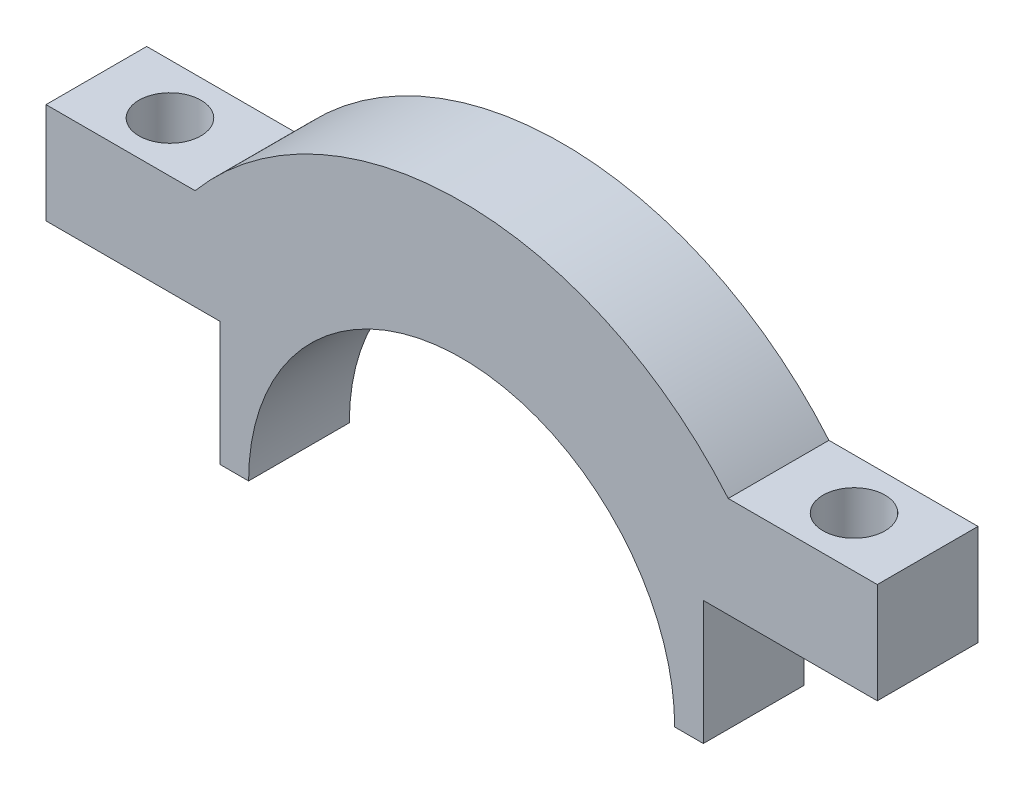
SolidWorks part; units mm, degrees
ref_plane "Front Plane" through (0, 0, 0) normal (0, 0, 1) x (1, 0, 0)
ref_plane "Top Plane" through (0, 0, 0) normal (0, 1, 0) x (1, 0, 0)
ref_plane "Right Plane" through (0, 0, 0) normal (1, 0, 0) x (0, 0, -1)
sketch "Sketch1" plane through (0, 0, 0) normal (0, 0, 1) x (1, 0, 0)
  line L0 (-27.5, 0) -> (-31.2, 0)
  line L1 (-31.2, 0) -> (-31.2, 16)
  line L2 (-31.2, 16) -> (-53.65, 16)
  line L3 (-53.65, 16) -> (-53.65, 29)
  line L4 (-53.65, 29) -> (-34.4093, 29)
  line L6 (27.5, 0) -> (31.2, 0)
  line L7 (31.2, 0) -> (31.2, 16)
  line L8 (31.2, 16) -> (53.65, 16)
  line L9 (53.65, 16) -> (53.65, 29)
  line L10 (53.65, 29) -> (34.4093, 29)
  arc A0 (27.5, 0) -> (-27.5, 0) centre (0, 0) ccw
  arc A1 (34.4093, 29) -> (-34.4093, 29) centre (0, 0) ccw
  dimension "D1" = 3.7
  dimension "D3" = 22.45
  dimension "D2" = 16
  dimension "D4" = 13
extrude "Boss-Extrude1" add sketch "Sketch1" against normal blind 13
sketch "Sketch3" plane through (0, 29, 0) normal (0, 1, 0) x (1, 0, 0)
  line L0 (-34.4093, 13) -> (-53.65, 13) construction
  line L1 (-53.65, 13) -> (-53.65, 0) construction
  line L2 (0, -9.0419) -> (0, 27.517) construction
  circle A0 centre (-44.15, 6.5) radius 4
  circle A1 centre (44.15, 6.5) radius 4
  dimension "D1" = 6.5
  dimension "D2" = 9.5
extrude "Cut-Extrude1" cut sketch "Sketch3" against normal up to surface (13 mm away) up to face at (-42.425, 16, -6.5)
